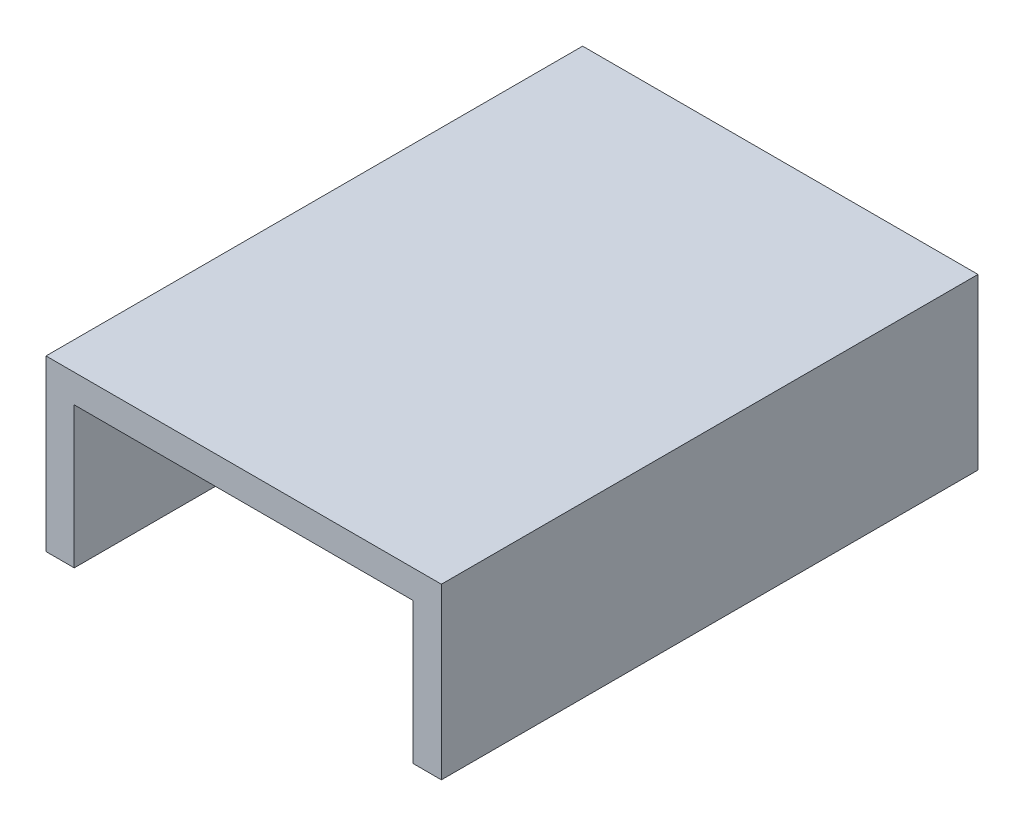
SolidWorks part; units mm, degrees
ref_plane "Front Plane" through (0, 0, 0) normal (0, 0, 1) x (1, 0, 0)
ref_plane "Top Plane" through (0, 0, 0) normal (0, 1, 0) x (1, 0, 0)
ref_plane "Right Plane" through (0, 0, 0) normal (1, 0, 0) x (0, 0, -1)
sketch "Sketch1" plane through (0, 0, 0) normal (0, 1, 0) x (1, 0, 0)
  line L1 (-35, -47.5) -> (35, -47.5)
  line L2 (-35, -47.5) -> (-35, 47.5)
  line L3 (-35, 47.5) -> (35, 47.5)
  line L4 (35, -47.5) -> (35, 47.5)
  line L5 (0, 47.5) -> (0, -47.5) construction
  line L6 (-35, 0) -> (35, 0) construction
  point P0 (0, 0)
  dimension "D1" = 70
  dimension "D2" = 95
extrude "Boss-Extrude1" add sketch "Sketch1" along normal blind 30
sketch "Sketch2" plane through (0, 0, 47.5) normal (0, 0, 1) x (1, 0, 0)
  line L0 (-35, 0) -> (35, 0) construction
  line L1 (-30, 0) -> (30, 0)
  line L2 (-30, 0) -> (-30, 25)
  line L3 (-30, 25) -> (30, 25)
  line L4 (30, 0) -> (30, 25)
  line L5 (35, 30) -> (35, 0) construction
  dimension "D1" = 25
  dimension "D2" = 60
  dimension "D3" = 5
extrude "Cut-Extrude1" cut sketch "Sketch2" against normal blind 87.5
